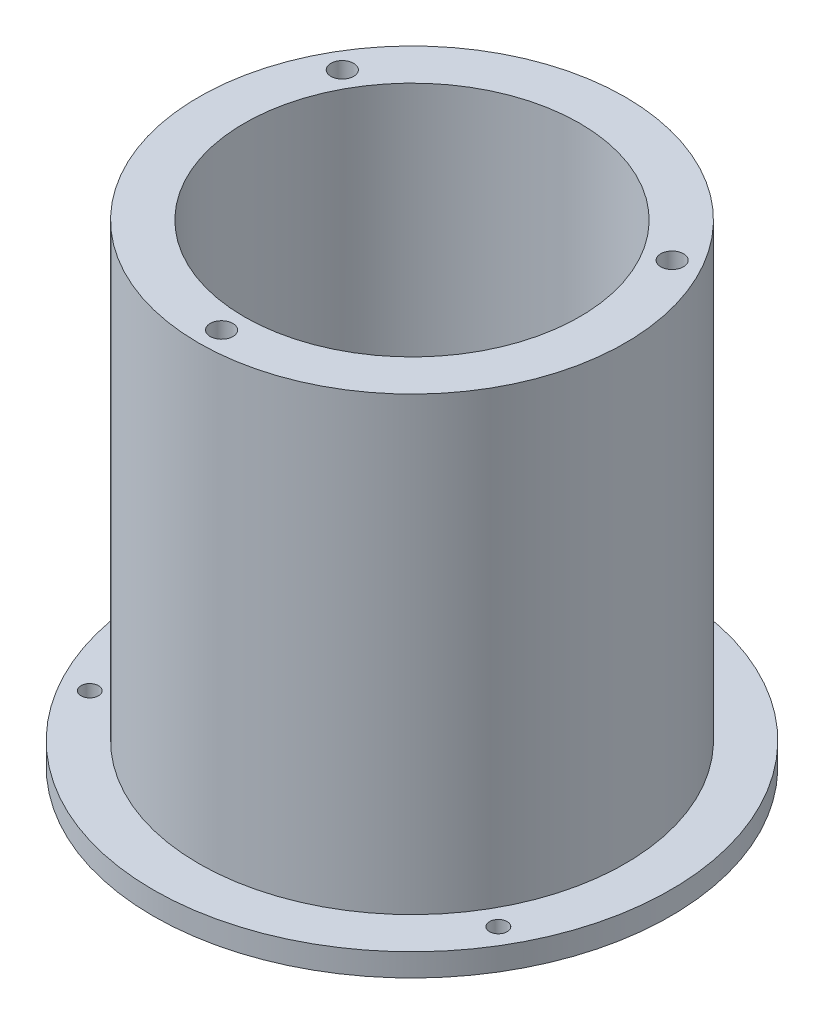
SolidWorks part; units mm, degrees
ref_plane "Front Plane" through (0, 0, 0) normal (0, 0, 1) x (1, 0, 0)
ref_plane "Top Plane" through (0, 0, 0) normal (0, 1, 0) x (1, 0, 0)
ref_plane "Right Plane" through (0, 0, 0) normal (1, 0, 0) x (0, 0, -1)
sketch "Sketch1" plane through (0, 0, 0) normal (0, 1, 0) x (1, 0, 0)
  circle A0 centre (0, 0) radius 45.5
  circle A1 centre (0, 0) radius 29.5
  dimension "D1" = 91
  dimension "D2" = 59
extrude "Boss-Extrude1" add sketch "Sketch1" along normal blind 4
sketch "Sketch2" plane through (0, 4, 0) normal (0, 1, 0) x (1, 0, 0)
  circle A0 centre (0, 0) radius 37.5
  circle A1 centre (0, 0) radius 29.5
extrude "Boss-Extrude2" add sketch "Sketch2" along normal blind 79.3
sketch "Sketch4" plane through (0, 4, 0) normal (0, 1, 0) x (1, 0, 0)
  circle A0 centre (0, 41.5) radius 1.55
  dimension "D1" = 3.1
  dimension "D2" = 41.5
extrude "Cut-Extrude1" cut sketch "Sketch4" against normal blind 83.3
pattern_circular "CirPattern1" count 3 over 360 about axis through (0, 0, 0) along (0, 1, 0) of "Cut-Extrude1"
sketch "Sketch6" plane through (0, 83.3, 0) normal (0, 1, 0) x (1, 0, 0)
  line L0 (0, 0) -> (0, 37.5) construction
  circle A0 centre (-29.0119, 16.75) radius 2
  circle A2 centre (0, 0) radius 37.5 construction
  dimension "D1" = 4
  dimension "D3" = 60
  dimension "D2" = 33.5
extrude "Cut-Extrude2" cut sketch "Sketch6" against normal blind 6
pattern_circular "CirPattern2" count 3 over 360 about axis through (0, 0, 0) along (0, 1, 0) of "Cut-Extrude2"
sketch "Sketch8" plane through (0, 0, 0) normal (0, -1, 0) x (1, 0, 0)
  circle A0 centre (0, 0) radius 30.5
  dimension "D1" = 61
extrude "Cut-Extrude4" cut sketch "Sketch8" against normal blind 6
